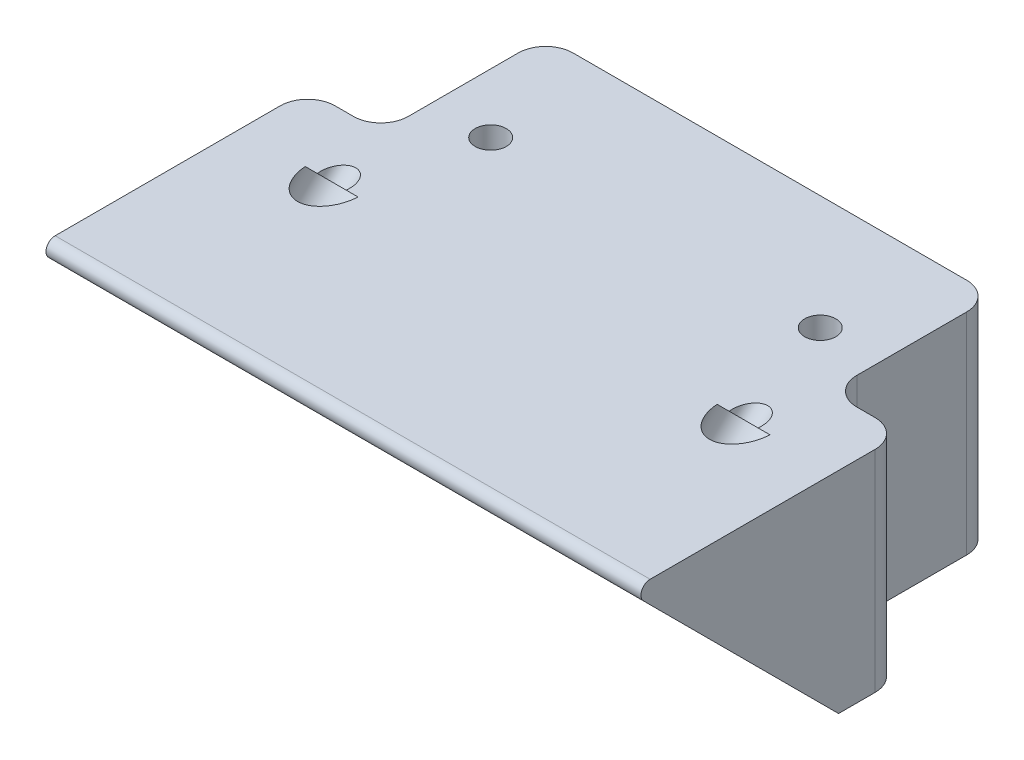
SolidWorks part; units mm, degrees
ref_plane "前视基准面" through (0, 0, 0) normal (0, 0, 1) x (1, 0, 0)
ref_plane "上视基准面" through (0, 0, 0) normal (0, 1, 0) x (1, 0, 0)
ref_plane "右视基准面" through (0, 0, 0) normal (1, 0, 0) x (0, 0, -1)
other "Configuration Table"
sketch "草图1" plane through (0, 0, 0) normal (0, 1, 0) x (1, 0, 0)
  line L1 (-32.5, -12.5) -> (32.5, -12.5)
  line L2 (-32.5, -12.5) -> (-32.5, 12.5)
  line L3 (-32.5, 12.5) -> (32.5, 12.5)
  line L4 (32.5, -12.5) -> (32.5, 12.5)
  line L5 (-32.5, -12.5) -> (32.5, 12.5) construction
  line L6 (-32.5, 12.5) -> (32.5, -12.5) construction
  point P0 (0, 0)
  dimension "D1" = 25
  dimension "D2" = 65
extrude "凸台-拉伸1" add sketch "草图1" along normal blind 23
sketch "草图2" plane through (32.5, 0, 0) normal (1, 0, 0) x (0, 0, -1)
  line L0 (-12.5, 0) -> (-35.5, 23)
  line L1 (-35.5, 23) -> (-12.5, 23)
  line L2 (-12.5, 23) -> (12.5, 23) construction
  line L3 (-12.5, 0) -> (-12.5, 23)
  dimension "D1" = 45
extrude "凸台-拉伸2" add sketch "草图2" against normal up to surface (65 mm away) up to face at (-32.5, 11.5, 0)
sketch "草图3" plane through (0, 0, 0) normal (0, -1, 0) x (1, 0, 0)
  line L0 (32.5, -12.5) -> (-32.5, -12.5) construction
  line L1 (-12.5, -12.5) -> (12.5, -12.5)
  line L2 (-12.5, -12.5) -> (-12.5, 7.5)
  line L3 (-12.5, 7.5) -> (12.5, 7.5)
  line L4 (12.5, -12.5) -> (12.5, 7.5)
  line L5 (0, 12.5) -> (0, -12.5) construction
  line L8 (-32.5, 12.5) -> (32.5, 12.5) construction
  dimension "D1" = 25
  dimension "D2" = 5
extrude "切除-拉伸1" cut sketch "草图3" against normal blind 18
sketch "草图4" plane through (0, -6.25, 6.25) normal (0, -0.7071, 0.7071) x (1, 0, 0)
  line L0 (0, 41.3657) -> (0, 8.8388) construction
  line L1 (-32.5, 41.3657) -> (32.5, 41.3657) construction
  line L2 (-32.5, 8.8388) -> (32.5, 8.8388) construction
  line L3 (-32.5, 25.1023) -> (32.5, 25.1023) construction
  line L4 (-32.5, 8.8388) -> (-32.5, 41.3657) construction
  line L5 (32.5, 41.3657) -> (32.5, 8.8388) construction
  circle A0 centre (-22.5, 25.1023) radius 1.6
  circle A1 centre (22.5, 25.1023) radius 1.6
  dimension "D1" = 3.2
  dimension "D2" = 45
extrude "切除-拉伸2" cut sketch "草图4" against normal through all both and the other way through all
sketch "草图5" plane through (0, -6.25, 6.25) normal (0, -0.7071, 0.7071) x (1, 0, 0)
  line L0 (0, 8.8388) -> (0, 41.3657) construction
  line L1 (-32.5, 8.8388) -> (32.5, 8.8388) construction
  line L2 (-32.5, 41.3657) -> (32.5, 41.3657) construction
  circle A0 centre (-22.5, 25.1023) radius 2.9
  circle A1 centre (22.5, 25.1023) radius 2.9
  dimension "D1" = 5.8
extrude "切除-拉伸3" cut sketch "草图5" against normal blind 9 from offset 7 offset against normal yes
sketch "草图6" plane through (0, 0, 0) normal (0, -1, 0) x (1, 0, 0)
  line L0 (-32.5, 0) -> (32.5, 0) construction
  line L1 (-32.5, -12.5) -> (-32.5, 12.5) construction
  line L2 (32.5, 12.5) -> (32.5, -12.5) construction
  line L3 (-18, -12.5) -> (-18, 12.5) construction
  line L5 (-32.5, 12.5) -> (32.5, 12.5) construction
  line L8 (0, -12.5) -> (0, 12.5) construction
  line L9 (-12.5, -12.5) -> (12.5, -12.5) construction
  circle A0 centre (-18, 7.5) radius 1.6 construction
  circle A1 centre (-18, 0) radius 1.7
  circle A2 centre (18, 0) radius 1.7
  point P8 (-18, 0)
  point P9 (-18, 0)
  dimension "D1" = 3.2
  dimension "D2" = 15
  dimension "D3" = 3.4
  dimension "D4" = 18
extrude "切除-拉伸4" cut sketch "草图6" against normal through all both and the other way through all
fillet "圆角1" radius 1 1 edges at (0, 23, 35.5)
sketch "草图7" plane through (0, 23, 0) normal (0, 1, 0) x (1, 0, 0)
  line L0 (0, 12.5) -> (0, -33.0858) construction
  line L1 (-32.5, 12.5) -> (-24.5, 12.5)
  line L2 (-32.5, 12.5) -> (-32.5, -5.5)
  line L3 (-32.5, -5.5) -> (-24.5, -5.5)
  line L4 (-24.5, 12.5) -> (-24.5, -5.5)
  line L5 (32.5, 12.5) -> (-32.5, 12.5) construction
  line L6 (-32.5, -33.0858) -> (32.5, -33.0858) construction
  line L7 (24.5, 12.5) -> (24.5, -5.5)
  line L8 (32.5, -5.5) -> (24.5, -5.5)
  line L9 (32.5, 12.5) -> (32.5, -5.5)
  line L10 (32.5, 12.5) -> (24.5, 12.5)
  dimension "D1" = 8
  dimension "D2" = 18
extrude "切除-拉伸5" cut sketch "草图7" against normal blind 40
fillet "圆角2" radius 3 6 edges at (-32.5, 11.5, 5.5) (-24.5, 11.5, -12.5) (-24.5, 11.5, 5.5) (32.5, 11.5, 5.5) (24.5, 11.5, -12.5) (24.5, 11.5, 5.5)
